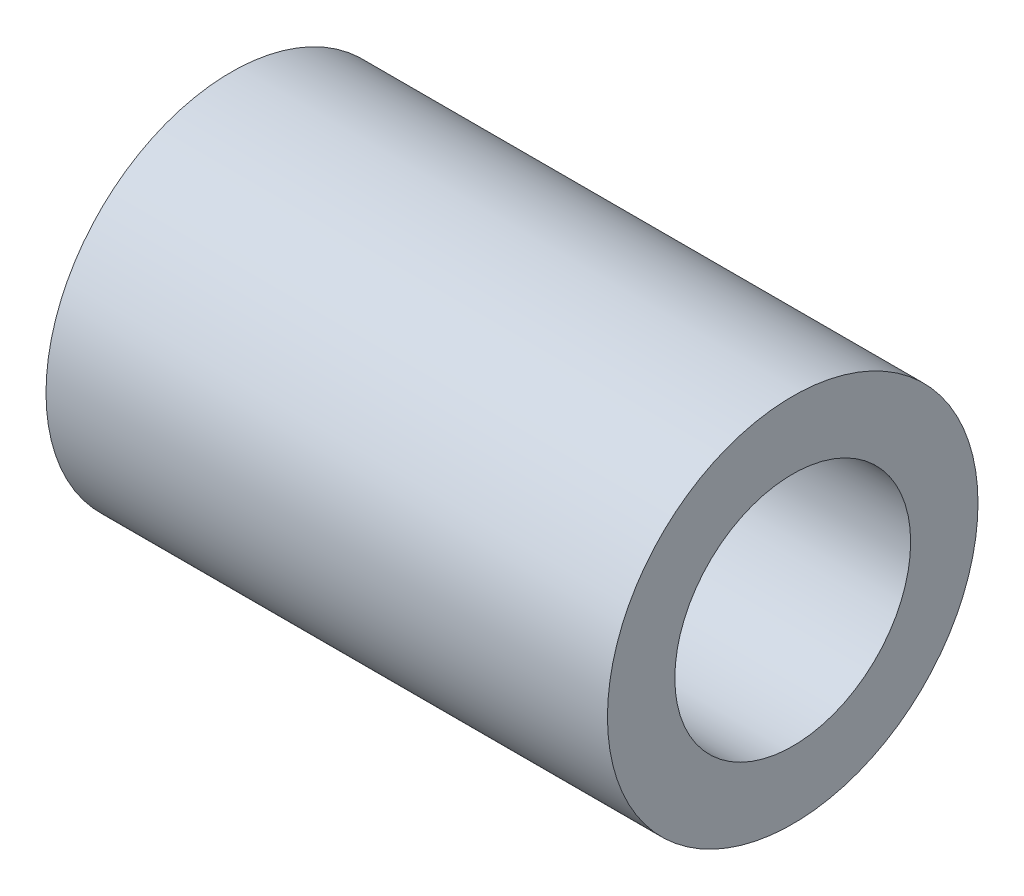
SolidWorks part; units mm, degrees
ref_plane "Front Plane" through (0, 0, 0) normal (0, 0, 1) x (1, 0, 0)
ref_plane "Top Plane" through (0, 0, 0) normal (0, 1, 0) x (1, 0, 0)
ref_plane "Right Plane" through (0, 0, 0) normal (1, 0, 0) x (0, 0, -1)
sketch "Sketch1" plane through (0, 0, 0) normal (1, 0, 0) x (0, 0, -1)
  circle A0 centre (0, 0) radius 2.1
  circle A1 centre (0, 0) radius 3.3
  dimension "D1" = 4.2
  dimension "D2" = 1.2
extrude "Boss-Extrude1" add sketch "Sketch1" along normal blind 10
